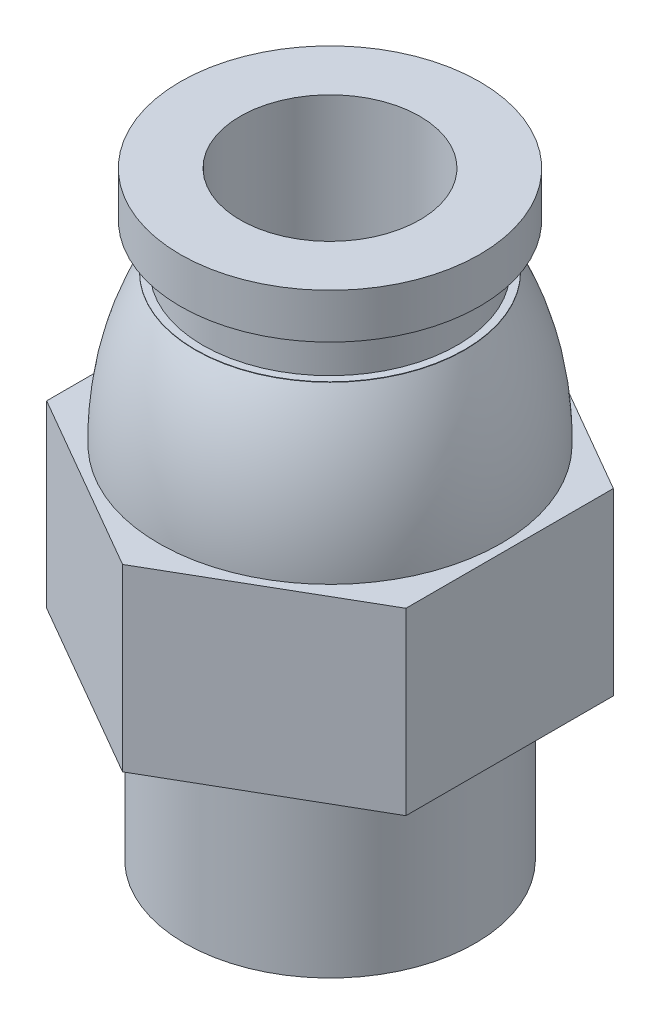
SolidWorks part; units mm, degrees
ref_plane "前视基准面" through (0, 0, 0) normal (0, 0, 1) x (1, 0, 0)
ref_plane "上视基准面" through (0, 0, 0) normal (0, 1, 0) x (1, 0, 0)
ref_plane "右视基准面" through (0, 0, 0) normal (1, 0, 0) x (0, 0, -1)
other "Configuration Table"
sketch "草图1" plane through (0, 0, 0) normal (0, 1, 0) x (1, 0, 0)
  circle A0 centre (0, 0) radius 4.85
  dimension "D1" = 9.7
extrude "凸台-拉伸1" add sketch "草图1" along normal blind 6
cosmetic thread "装饰螺纹线1" parameters "D2"=8.566
sketch "草图2" plane through (0, 6, 0) normal (0, 1, 0) x (1, 0, 0)
  line L1 (6, 3.4641) -> (0, 6.9282)
  line L2 (0, 6.9282) -> (-6, 3.4641)
  line L3 (-6, 3.4641) -> (-6, -3.4641)
  line L4 (-6, -3.4641) -> (0, -6.9282)
  line L5 (0, -6.9282) -> (6, -3.4641)
  line L6 (6, -3.4641) -> (6, 3.4641)
  circle A0 centre (0, 0) radius 6 construction
  dimension "D1" = 12
extrude "凸台-拉伸2" add sketch "草图2" along normal blind 6
sketch "草图3" plane through (0, 12, 0) normal (0, 1, 0) x (1, 0, 0)
  circle A0 centre (0, 0) radius 4.5
  dimension "D1" = 9
extrude "凸台-拉伸3" add sketch "草图3" along normal blind 5
sketch "草图4" plane through (0, 17, 0) normal (0, 1, 0) x (1, 0, 0)
  circle A0 centre (0, 0) radius 4.25
  dimension "D1" = 8.5
extrude "凸台-拉伸4" add sketch "草图4" along normal blind 1
sketch "草图5" plane through (0, 18, 0) normal (0, 1, 0) x (1, 0, 0)
  circle A0 centre (0, 0) radius 3.75
  dimension "D1" = 7.5
extrude "凸台-拉伸5" add sketch "草图5" along normal blind 0.5
sketch "草图6" plane through (0, 18.5, 0) normal (0, 1, 0) x (1, 0, 0)
  circle A0 centre (0, 0) radius 5
  dimension "D1" = 10
extrude "凸台-拉伸6" add sketch "草图6" along normal blind 1.5
sketch "草图7" plane through (0, 0, 0) normal (0, 0, 1) x (1, 0, 0)
  line L0 (-4.5, 17) -> (-4.5, 12) construction
  line L1 (-6, 12) -> (0, 12) construction
  line L2 (-5.7161, 12) -> (-4.5, 12)
  line L3 (-4.5, 12) -> (-4.5, 16.9863)
  line L4 (0, 12) -> (0, 16.7375) construction
  spline S0 degree 2 poles (-4.5, 16.9863) (-5.7568, 14.6776) (-5.7161, 12) knots 0 0 0 1 1 1
revolve "旋转1" add sketch "草图7" angle 360 about L4
sketch "草图11" plane through (0, 0, 0) normal (0, -1, 0) x (-1, 0, 0)
  point P0 (0, 0)
hole_wizard "Ø6.0mm 暗销孔1" positions "草图11" profile "草图10" hole size "Ø6.0" standard "GB" end condition through all
sketch "草图10" plane through (0, 0, 0) normal (1, 0, 0) x (0, 0, -1)
  line L0 (0, 0) -> (0, 20)
  line L1 (0, 20) -> (3, 20)
  line L2 (3, 20) -> (3, 0.025)
  line L3 (3, 0.025) -> (3.025, 0)
  line L5 (3.025, 0) -> (0, 0)
  line L6 (-3, 0.025) -> (-3.025, 0) construction
  line L11 (0, -6.35) -> (0, 107.95) construction
  dimension "通孔孔直径" = 6
  dimension "通孔孔深度" = 20
  dimension "近端锥形沉头孔直径" = 6.05
  dimension "近端锥形沉头孔角度" = 90
